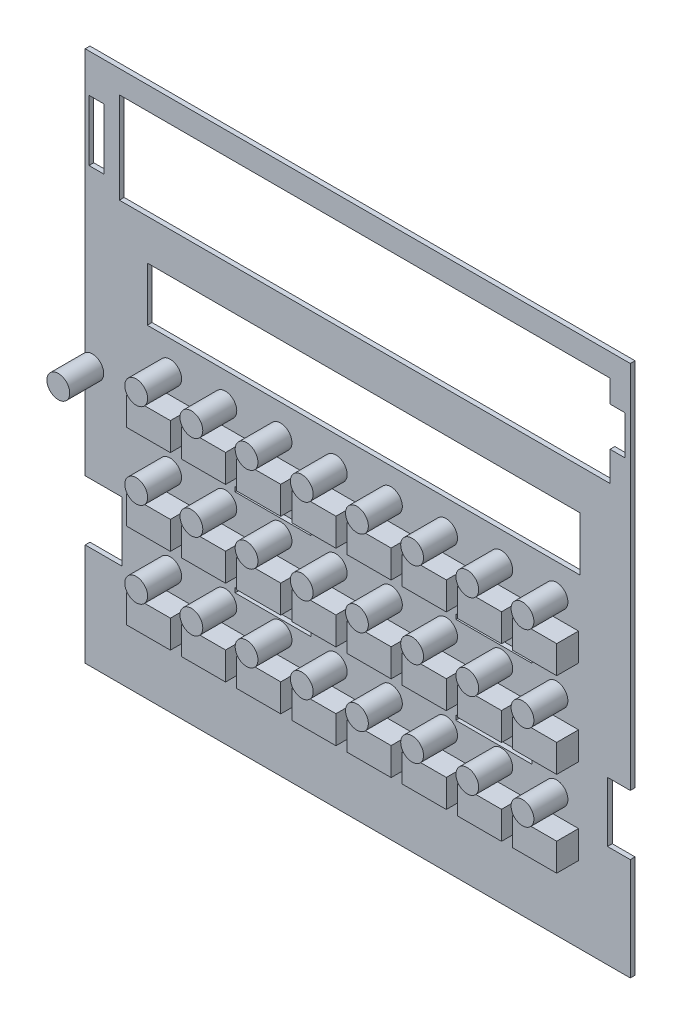
SolidWorks part; units mm, degrees
ref_plane "Front Plane" through (0, 0, 0) normal (0, 0, 1) x (1, 0, 0)
ref_plane "Top Plane" through (0, 0, 0) normal (0, 1, 0) x (1, 0, 0)
ref_plane "Right Plane" through (0, 0, 0) normal (1, 0, 0) x (0, 0, -1)
sketch "Sketch1" plane through (0, 0, 0) normal (0, 0, 1) x (1, 0, 0)
  line L0 (0, 0) -> (182.118, 0)
  line L1 (182.118, 0) -> (182.118, 34.2468)
  line L2 (182.118, 34.2468) -> (174.498, 34.2468)
  line L3 (174.498, 34.2468) -> (174.498, 54.2468)
  line L4 (174.498, 54.2468) -> (182.118, 54.2468)
  line L5 (182.118, 54.2468) -> (182.118, 177.8)
  line L6 (182.118, 177.8) -> (0, 177.8)
  line L7 (0, 177.8) -> (0, 54.2468)
  line L8 (0, 54.2468) -> (7.62, 54.2468)
  line L9 (7.62, 54.2468) -> (12.3749, 54.2468)
  line L10 (12.3749, 54.2468) -> (12.3825, 54.2392)
  line L11 (12.3825, 54.2392) -> (12.3825, 34.2392)
  line L12 (12.3825, 34.2392) -> (12.3749, 34.2468)
  line L13 (12.3749, 34.2468) -> (7.62, 34.2468)
  line L14 (7.62, 34.2468) -> (0, 34.2468)
  line L15 (0, 34.2468) -> (0, 0)
  line L16 (20.7391, 108.1786) -> (20.7391, 126.1796)
  line L17 (20.7391, 126.1796) -> (165.3007, 126.1796)
  line L18 (165.3007, 126.1796) -> (165.3007, 108.1786)
  line L19 (165.3007, 108.1786) -> (20.7391, 108.1786)
  line L20 (1.27, 144.653) -> (1.27, 164.973)
  line L21 (1.27, 164.973) -> (6.35, 164.973)
  line L22 (6.35, 164.973) -> (6.35, 144.653)
  line L23 (6.35, 144.653) -> (1.27, 144.653)
  line L24 (12.7, 170.18) -> (175.26, 170.18)
  line L25 (175.26, 170.18) -> (175.26, 162.6616)
  line L26 (175.26, 162.6616) -> (180.086, 162.6616)
  line L27 (180.086, 162.6616) -> (180.2892, 162.4584)
  line L28 (180.2892, 162.4584) -> (180.2892, 149.606)
  line L29 (180.2892, 149.606) -> (175.3616, 149.606)
  line L30 (175.3616, 149.606) -> (175.26, 149.5044)
  line L31 (175.26, 149.5044) -> (175.26, 139.7)
  line L32 (175.26, 139.7) -> (12.7, 139.7)
  line L33 (12.7, 139.7) -> (11.43, 139.7)
  line L34 (11.43, 139.7) -> (11.43, 170.18)
  line L35 (11.43, 170.18) -> (12.7, 170.18)
  line L36 (50.0634, 45.4152) -> (50.0634, 47.0027)
  line L37 (50.0634, 47.0027) -> (75.4634, 47.0027)
  line L38 (75.4634, 47.0027) -> (75.4634, 45.4152)
  line L39 (75.4634, 45.4152) -> (50.0634, 45.4152)
  line L40 (123.8134, 45.4152) -> (123.8134, 47.0027)
  line L41 (123.8134, 47.0027) -> (149.2134, 47.0027)
  line L42 (149.2134, 47.0027) -> (149.2134, 45.4152)
  line L43 (149.2134, 45.4152) -> (123.8134, 45.4152)
  line L44 (123.8134, 74.6252) -> (123.8134, 76.2127)
  line L45 (123.8134, 76.2127) -> (149.2134, 76.2127)
  line L46 (149.2134, 76.2127) -> (149.2134, 74.6252)
  line L47 (149.2134, 74.6252) -> (123.8134, 74.6252)
  line L48 (50.0634, 74.6252) -> (50.0634, 76.2127)
  line L49 (50.0634, 76.2127) -> (75.4634, 76.2127)
  line L50 (75.4634, 76.2127) -> (75.4634, 74.6252)
  line L51 (75.4634, 74.6252) -> (50.0634, 74.6252)
extrude "BOARD" add sketch "Sketch1" along normal blind 1.5921 separate body
ref_plane "Plane1" through (0, 0, 1.5921) normal (0, 0, 1) x (1, 0, 0)
sketch "Sketch2" plane through (0, 0, 1.5921) normal (0, 0, 1) x (1, 0, 0)
  circle A0 centre (2.3825, 86.9188) radius 3.81
extrude "LED-KINGBRIGHT_3P_2P54-1" add sketch "Sketch2" along normal blind 11.3538 separate body
sketch "Sketch3" plane through (0, 0, 1.5921) normal (0, 0, 1) x (1, 0, 0)
  circle A0 centre (157.4597, 41.1988) radius 3.81
extrude "LED-KINGBRIGHT_3P_2P54-2" add sketch "Sketch3" along normal blind 11.3538 separate body
sketch "Sketch4" plane through (0, 0, 1.5921) normal (0, 0, 1) x (1, 0, 0)
  circle A0 centre (139.0222, 41.1988) radius 3.81
extrude "LED-KINGBRIGHT_3P_2P54-3" add sketch "Sketch4" along normal blind 11.3538 separate body
sketch "Sketch5" plane through (0, 0, 1.5921) normal (0, 0, 1) x (1, 0, 0)
  circle A0 centre (120.5847, 41.1988) radius 3.81
extrude "LED-KINGBRIGHT_3P_2P54-4" add sketch "Sketch5" along normal blind 11.3538 separate body
sketch "Sketch6" plane through (0, 0, 1.5921) normal (0, 0, 1) x (1, 0, 0)
  circle A0 centre (102.1472, 41.1988) radius 3.81
extrude "LED-KINGBRIGHT_3P_2P54-5" add sketch "Sketch6" along normal blind 11.3538 separate body
sketch "Sketch7" plane through (0, 0, 1.5921) normal (0, 0, 1) x (1, 0, 0)
  circle A0 centre (157.4597, 69.7738) radius 3.81
extrude "LED-KINGBRIGHT_3P_2P54-6" add sketch "Sketch7" along normal blind 11.3538 separate body
sketch "Sketch8" plane through (0, 0, 1.5921) normal (0, 0, 1) x (1, 0, 0)
  circle A0 centre (139.0222, 69.7738) radius 3.81
extrude "LED-KINGBRIGHT_3P_2P54-7" add sketch "Sketch8" along normal blind 11.3538 separate body
sketch "Sketch9" plane through (0, 0, 1.5921) normal (0, 0, 1) x (1, 0, 0)
  circle A0 centre (120.5847, 69.7738) radius 3.81
extrude "LED-KINGBRIGHT_3P_2P54-8" add sketch "Sketch9" along normal blind 11.3538 separate body
sketch "Sketch10" plane through (0, 0, 1.5921) normal (0, 0, 1) x (1, 0, 0)
  circle A0 centre (102.1472, 69.7738) radius 3.81
extrude "LED-KINGBRIGHT_3P_2P54-9" add sketch "Sketch10" along normal blind 11.3538 separate body
sketch "Sketch11" plane through (0, 0, 1.5921) normal (0, 0, 1) x (1, 0, 0)
  circle A0 centre (83.7097, 41.1988) radius 3.81
extrude "LED-KINGBRIGHT_3P_2P54-10" add sketch "Sketch11" along normal blind 11.3538 separate body
sketch "Sketch12" plane through (0, 0, 1.5921) normal (0, 0, 1) x (1, 0, 0)
  circle A0 centre (65.2722, 41.1988) radius 3.81
extrude "LED-KINGBRIGHT_3P_2P54-11" add sketch "Sketch12" along normal blind 11.3538 separate body
sketch "Sketch13" plane through (0, 0, 1.5921) normal (0, 0, 1) x (1, 0, 0)
  circle A0 centre (46.8347, 41.1988) radius 3.81
extrude "LED-KINGBRIGHT_3P_2P54-12" add sketch "Sketch13" along normal blind 11.3538 separate body
sketch "Sketch14" plane through (0, 0, 1.5921) normal (0, 0, 1) x (1, 0, 0)
  circle A0 centre (28.3972, 41.1988) radius 3.81
extrude "LED-KINGBRIGHT_3P_2P54-13" add sketch "Sketch14" along normal blind 11.3538 separate body
sketch "Sketch15" plane through (0, 0, 1.5921) normal (0, 0, 1) x (1, 0, 0)
  circle A0 centre (83.7097, 69.7738) radius 3.81
extrude "LED-KINGBRIGHT_3P_2P54-14" add sketch "Sketch15" along normal blind 11.3538 separate body
sketch "Sketch16" plane through (0, 0, 1.5921) normal (0, 0, 1) x (1, 0, 0)
  circle A0 centre (65.2722, 69.7738) radius 3.81
extrude "LED-KINGBRIGHT_3P_2P54-15" add sketch "Sketch16" along normal blind 11.3538 separate body
sketch "Sketch17" plane through (0, 0, 1.5921) normal (0, 0, 1) x (1, 0, 0)
  circle A0 centre (46.8347, 69.7738) radius 3.81
extrude "LED-KINGBRIGHT_3P_2P54-16" add sketch "Sketch17" along normal blind 11.3538 separate body
sketch "Sketch18" plane through (0, 0, 1.5921) normal (0, 0, 1) x (1, 0, 0)
  circle A0 centre (28.3972, 69.7738) radius 3.81
extrude "LED-KINGBRIGHT_3P_2P54-17" add sketch "Sketch18" along normal blind 11.3538 separate body
sketch "Sketch19" plane through (0, 0, 1.5921) normal (0, 0, 1) x (1, 0, 0)
  circle A0 centre (157.4597, 98.3488) radius 3.81
extrude "LED-KINGBRIGHT_3P_2P54-18" add sketch "Sketch19" along normal blind 11.3538 separate body
sketch "Sketch20" plane through (0, 0, 1.5921) normal (0, 0, 1) x (1, 0, 0)
  circle A0 centre (139.0222, 98.3488) radius 3.81
extrude "LED-KINGBRIGHT_3P_2P54-19" add sketch "Sketch20" along normal blind 11.3538 separate body
sketch "Sketch21" plane through (0, 0, 1.5921) normal (0, 0, 1) x (1, 0, 0)
  circle A0 centre (120.5847, 98.3488) radius 3.81
extrude "LED-KINGBRIGHT_3P_2P54-20" add sketch "Sketch21" along normal blind 11.3538 separate body
sketch "Sketch22" plane through (0, 0, 1.5921) normal (0, 0, 1) x (1, 0, 0)
  circle A0 centre (102.1472, 98.3488) radius 3.81
extrude "LED-KINGBRIGHT_3P_2P54-21" add sketch "Sketch22" along normal blind 11.3538 separate body
sketch "Sketch23" plane through (0, 0, 1.5921) normal (0, 0, 1) x (1, 0, 0)
  circle A0 centre (83.7097, 98.3488) radius 3.81
extrude "LED-KINGBRIGHT_3P_2P54-22" add sketch "Sketch23" along normal blind 11.3538 separate body
sketch "Sketch24" plane through (0, 0, 1.5921) normal (0, 0, 1) x (1, 0, 0)
  circle A0 centre (65.2722, 98.3488) radius 3.81
extrude "LED-KINGBRIGHT_3P_2P54-23" add sketch "Sketch24" along normal blind 11.3538 separate body
sketch "Sketch25" plane through (0, 0, 1.5921) normal (0, 0, 1) x (1, 0, 0)
  circle A0 centre (46.8347, 98.3488) radius 3.81
extrude "LED-KINGBRIGHT_3P_2P54-24" add sketch "Sketch25" along normal blind 11.3538 separate body
sketch "Sketch26" plane through (0, 0, 1.5921) normal (0, 0, 1) x (1, 0, 0)
  circle A0 centre (28.3972, 98.3488) radius 3.81
extrude "LED-KINGBRIGHT_3P_2P54-25" add sketch "Sketch26" along normal blind 11.3538 separate body
sketch "Sketch27" plane through (0, 0, 1.5921) normal (0, 0, 1) x (1, 0, 0)
  line L0 (150.0937, 25.3238) -> (150.0937, 34.5948)
  line L1 (150.0937, 34.5948) -> (164.8257, 34.5948)
  line L2 (164.8257, 34.5948) -> (164.8257, 25.3238)
  line L3 (164.8257, 25.3238) -> (150.0937, 25.3238)
extrude "SWITCH-MCDTS2-1" add sketch "Sketch27" along normal blind 7.3 separate body
sketch "Sketch28" plane through (0, 0, 1.5921) normal (0, 0, 1) x (1, 0, 0)
  line L0 (150.0937, 53.8988) -> (150.0937, 63.1698)
  line L1 (150.0937, 63.1698) -> (164.8257, 63.1698)
  line L2 (164.8257, 63.1698) -> (164.8257, 53.8988)
  line L3 (164.8257, 53.8988) -> (150.0937, 53.8988)
extrude "SWITCH-MCDTS2-2" add sketch "Sketch28" along normal blind 7.3 separate body
sketch "Sketch29" plane through (0, 0, 1.5921) normal (0, 0, 1) x (1, 0, 0)
  line L0 (131.6562, 25.3238) -> (131.6562, 34.5948)
  line L1 (131.6562, 34.5948) -> (146.3882, 34.5948)
  line L2 (146.3882, 34.5948) -> (146.3882, 25.3238)
  line L3 (146.3882, 25.3238) -> (131.6562, 25.3238)
extrude "SWITCH-MCDTS2-3" add sketch "Sketch29" along normal blind 7.3 separate body
sketch "Sketch30" plane through (0, 0, 1.5921) normal (0, 0, 1) x (1, 0, 0)
  line L0 (113.2187, 25.3238) -> (113.2187, 34.5948)
  line L1 (113.2187, 34.5948) -> (127.9507, 34.5948)
  line L2 (127.9507, 34.5948) -> (127.9507, 25.3238)
  line L3 (127.9507, 25.3238) -> (113.2187, 25.3238)
extrude "SWITCH-MCDTS2-4" add sketch "Sketch30" along normal blind 7.3 separate body
sketch "Sketch31" plane through (0, 0, 1.5921) normal (0, 0, 1) x (1, 0, 0)
  line L0 (94.7812, 25.3238) -> (94.7812, 34.5948)
  line L1 (94.7812, 34.5948) -> (109.5132, 34.5948)
  line L2 (109.5132, 34.5948) -> (109.5132, 25.3238)
  line L3 (109.5132, 25.3238) -> (94.7812, 25.3238)
extrude "SWITCH-MCDTS2-5" add sketch "Sketch31" along normal blind 7.3 separate body
sketch "Sketch32" plane through (0, 0, 1.5921) normal (0, 0, 1) x (1, 0, 0)
  line L0 (76.3437, 25.3238) -> (76.3437, 34.5948)
  line L1 (76.3437, 34.5948) -> (91.0757, 34.5948)
  line L2 (91.0757, 34.5948) -> (91.0757, 25.3238)
  line L3 (91.0757, 25.3238) -> (76.3437, 25.3238)
extrude "SWITCH-MCDTS2-6" add sketch "Sketch32" along normal blind 7.3 separate body
sketch "Sketch33" plane through (0, 0, 1.5921) normal (0, 0, 1) x (1, 0, 0)
  line L0 (57.9062, 25.3238) -> (57.9062, 34.5948)
  line L1 (57.9062, 34.5948) -> (72.6382, 34.5948)
  line L2 (72.6382, 34.5948) -> (72.6382, 25.3238)
  line L3 (72.6382, 25.3238) -> (57.9062, 25.3238)
extrude "SWITCH-MCDTS2-7" add sketch "Sketch33" along normal blind 7.3 separate body
sketch "Sketch34" plane through (0, 0, 1.5921) normal (0, 0, 1) x (1, 0, 0)
  line L0 (39.4687, 25.3238) -> (39.4687, 34.5948)
  line L1 (39.4687, 34.5948) -> (54.2007, 34.5948)
  line L2 (54.2007, 34.5948) -> (54.2007, 25.3238)
  line L3 (54.2007, 25.3238) -> (39.4687, 25.3238)
extrude "SWITCH-MCDTS2-8" add sketch "Sketch34" along normal blind 7.3 separate body
sketch "Sketch35" plane through (0, 0, 1.5921) normal (0, 0, 1) x (1, 0, 0)
  line L0 (21.0312, 25.3238) -> (21.0312, 34.5948)
  line L1 (21.0312, 34.5948) -> (35.7632, 34.5948)
  line L2 (35.7632, 34.5948) -> (35.7632, 25.3238)
  line L3 (35.7632, 25.3238) -> (21.0312, 25.3238)
extrude "SWITCH-MCDTS2-9" add sketch "Sketch35" along normal blind 7.3 separate body
sketch "Sketch36" plane through (0, 0, 1.5921) normal (0, 0, 1) x (1, 0, 0)
  line L0 (131.6562, 53.8988) -> (131.6562, 63.1698)
  line L1 (131.6562, 63.1698) -> (146.3882, 63.1698)
  line L2 (146.3882, 63.1698) -> (146.3882, 53.8988)
  line L3 (146.3882, 53.8988) -> (131.6562, 53.8988)
extrude "SWITCH-MCDTS2-10" add sketch "Sketch36" along normal blind 7.3 separate body
sketch "Sketch37" plane through (0, 0, 1.5921) normal (0, 0, 1) x (1, 0, 0)
  line L0 (113.2187, 53.8988) -> (113.2187, 63.1698)
  line L1 (113.2187, 63.1698) -> (127.9507, 63.1698)
  line L2 (127.9507, 63.1698) -> (127.9507, 53.8988)
  line L3 (127.9507, 53.8988) -> (113.2187, 53.8988)
extrude "SWITCH-MCDTS2-11" add sketch "Sketch37" along normal blind 7.3 separate body
sketch "Sketch38" plane through (0, 0, 1.5921) normal (0, 0, 1) x (1, 0, 0)
  line L0 (94.7812, 53.8988) -> (94.7812, 63.1698)
  line L1 (94.7812, 63.1698) -> (109.5132, 63.1698)
  line L2 (109.5132, 63.1698) -> (109.5132, 53.8988)
  line L3 (109.5132, 53.8988) -> (94.7812, 53.8988)
extrude "SWITCH-MCDTS2-12" add sketch "Sketch38" along normal blind 7.3 separate body
sketch "Sketch39" plane through (0, 0, 1.5921) normal (0, 0, 1) x (1, 0, 0)
  line L0 (76.3437, 53.8988) -> (76.3437, 63.1698)
  line L1 (76.3437, 63.1698) -> (91.0757, 63.1698)
  line L2 (91.0757, 63.1698) -> (91.0757, 53.8988)
  line L3 (91.0757, 53.8988) -> (76.3437, 53.8988)
extrude "SWITCH-MCDTS2-13" add sketch "Sketch39" along normal blind 7.3 separate body
sketch "Sketch40" plane through (0, 0, 1.5921) normal (0, 0, 1) x (1, 0, 0)
  line L0 (57.9062, 53.8988) -> (57.9062, 63.1698)
  line L1 (57.9062, 63.1698) -> (72.6382, 63.1698)
  line L2 (72.6382, 63.1698) -> (72.6382, 53.8988)
  line L3 (72.6382, 53.8988) -> (57.9062, 53.8988)
extrude "SWITCH-MCDTS2-14" add sketch "Sketch40" along normal blind 7.3 separate body
sketch "Sketch41" plane through (0, 0, 1.5921) normal (0, 0, 1) x (1, 0, 0)
  line L0 (39.4687, 53.8988) -> (39.4687, 63.1698)
  line L1 (39.4687, 63.1698) -> (54.2007, 63.1698)
  line L2 (54.2007, 63.1698) -> (54.2007, 53.8988)
  line L3 (54.2007, 53.8988) -> (39.4687, 53.8988)
extrude "SWITCH-MCDTS2-15" add sketch "Sketch41" along normal blind 7.3 separate body
sketch "Sketch42" plane through (0, 0, 1.5921) normal (0, 0, 1) x (1, 0, 0)
  line L0 (21.0312, 53.8988) -> (21.0312, 63.1698)
  line L1 (21.0312, 63.1698) -> (35.7632, 63.1698)
  line L2 (35.7632, 63.1698) -> (35.7632, 53.8988)
  line L3 (35.7632, 53.8988) -> (21.0312, 53.8988)
extrude "SWITCH-MCDTS2-16" add sketch "Sketch42" along normal blind 7.3 separate body
sketch "Sketch43" plane through (0, 0, 1.5921) normal (0, 0, 1) x (1, 0, 0)
  line L0 (150.0937, 82.4738) -> (150.0937, 91.7448)
  line L1 (150.0937, 91.7448) -> (164.8257, 91.7448)
  line L2 (164.8257, 91.7448) -> (164.8257, 82.4738)
  line L3 (164.8257, 82.4738) -> (150.0937, 82.4738)
extrude "SWITCH-MCDTS2-17" add sketch "Sketch43" along normal blind 7.3 separate body
sketch "Sketch44" plane through (0, 0, 1.5921) normal (0, 0, 1) x (1, 0, 0)
  line L0 (131.6562, 82.4738) -> (131.6562, 91.7448)
  line L1 (131.6562, 91.7448) -> (146.3882, 91.7448)
  line L2 (146.3882, 91.7448) -> (146.3882, 82.4738)
  line L3 (146.3882, 82.4738) -> (131.6562, 82.4738)
extrude "SWITCH-MCDTS2-18" add sketch "Sketch44" along normal blind 7.3 separate body
sketch "Sketch45" plane through (0, 0, 1.5921) normal (0, 0, 1) x (1, 0, 0)
  line L0 (113.2187, 82.4738) -> (113.2187, 91.7448)
  line L1 (113.2187, 91.7448) -> (127.9507, 91.7448)
  line L2 (127.9507, 91.7448) -> (127.9507, 82.4738)
  line L3 (127.9507, 82.4738) -> (113.2187, 82.4738)
extrude "SWITCH-MCDTS2-19" add sketch "Sketch45" along normal blind 7.3 separate body
sketch "Sketch46" plane through (0, 0, 1.5921) normal (0, 0, 1) x (1, 0, 0)
  line L0 (94.7812, 82.4738) -> (94.7812, 91.7448)
  line L1 (94.7812, 91.7448) -> (109.5132, 91.7448)
  line L2 (109.5132, 91.7448) -> (109.5132, 82.4738)
  line L3 (109.5132, 82.4738) -> (94.7812, 82.4738)
extrude "SWITCH-MCDTS2-20" add sketch "Sketch46" along normal blind 7.3 separate body
sketch "Sketch47" plane through (0, 0, 1.5921) normal (0, 0, 1) x (1, 0, 0)
  line L0 (76.3437, 82.4738) -> (76.3437, 91.7448)
  line L1 (76.3437, 91.7448) -> (91.0757, 91.7448)
  line L2 (91.0757, 91.7448) -> (91.0757, 82.4738)
  line L3 (91.0757, 82.4738) -> (76.3437, 82.4738)
extrude "SWITCH-MCDTS2-21" add sketch "Sketch47" along normal blind 7.3 separate body
sketch "Sketch48" plane through (0, 0, 1.5921) normal (0, 0, 1) x (1, 0, 0)
  line L0 (57.9062, 82.4738) -> (57.9062, 91.7448)
  line L1 (57.9062, 91.7448) -> (72.6382, 91.7448)
  line L2 (72.6382, 91.7448) -> (72.6382, 82.4738)
  line L3 (72.6382, 82.4738) -> (57.9062, 82.4738)
extrude "SWITCH-MCDTS2-22" add sketch "Sketch48" along normal blind 7.3 separate body
sketch "Sketch49" plane through (0, 0, 1.5921) normal (0, 0, 1) x (1, 0, 0)
  line L0 (39.4687, 82.4738) -> (39.4687, 91.7448)
  line L1 (39.4687, 91.7448) -> (54.2007, 91.7448)
  line L2 (54.2007, 91.7448) -> (54.2007, 82.4738)
  line L3 (54.2007, 82.4738) -> (39.4687, 82.4738)
extrude "SWITCH-MCDTS2-23" add sketch "Sketch49" along normal blind 7.3 separate body
sketch "Sketch50" plane through (0, 0, 1.5921) normal (0, 0, 1) x (1, 0, 0)
  line L0 (21.0312, 82.4738) -> (21.0312, 91.7448)
  line L1 (21.0312, 91.7448) -> (35.7632, 91.7448)
  line L2 (35.7632, 91.7448) -> (35.7632, 82.4738)
  line L3 (35.7632, 82.4738) -> (21.0312, 82.4738)
extrude "SWITCH-MCDTS2-24" add sketch "Sketch50" along normal blind 7.3 separate body
